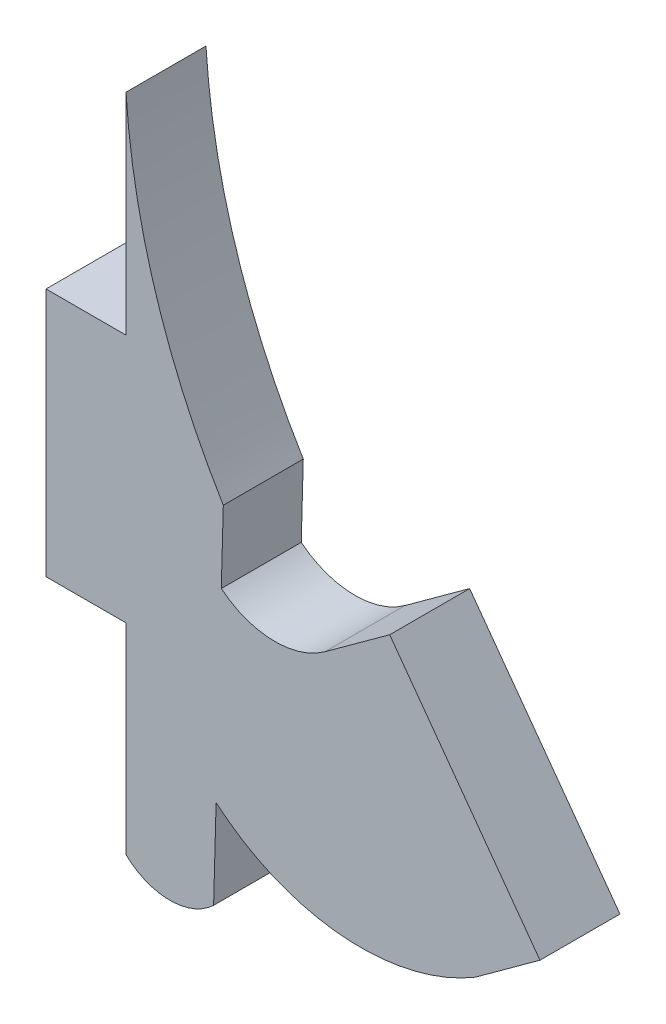
SolidWorks part; units mm, degrees
ref_plane "Front Plane" through (0, 0, 0) normal (0, 0, 1) x (1, 0, 0)
ref_plane "Top Plane" through (0, 0, 0) normal (0, 1, 0) x (1, 0, 0)
ref_plane "Right Plane" through (0, 0, 0) normal (1, 0, 0) x (0, 0, -1)
sketch "Sketch1" plane through (0, 0, 0) normal (0, 0, 1) x (1, 0, 0)
  line L0 (1.524, 26.9677) -> (0, 26.9677)
  line L1 (0, 26.9677) -> (0, 22.2179)
  line L2 (0, 22.2179) -> (1.524, 22.2179)
  line L3 (1.524, 22.2179) -> (1.524, 18.3913)
  line L4 (1.524, 26.9677) -> (1.524, 30.9774)
  line L5 (3.1937, 18.3913) -> (3.2411, 20.1101)
  line L6 (3.3399, 23.6931) -> (3.3784, 25.0875)
  line L7 (8.1815, 19.6991) -> (9.414, 20.5955)
  line L8 (6.5491, 24.5349) -> (9.414, 20.5955)
  line L9 (5.3165, 23.6386) -> (6.5491, 24.5349)
  arc A0 (1.524, 30.9774) -> (3.3784, 25.0875) centre (14.4741, 31.8177) ccw
  arc A1 (1.524, 18.3913) -> (3.1937, 18.3913) centre (2.3589, 19.2679) ccw
  arc A2 (3.2411, 20.1101) -> (8.1815, 19.6991) centre (5.9982, 23.3531) ccw
  arc A3 (3.3399, 23.6931) -> (5.3165, 23.6386) centre (4.3636, 24.9489) ccw
extrude "Boss-Extrude1" add sketch "Sketch1" along normal blind 1.524
